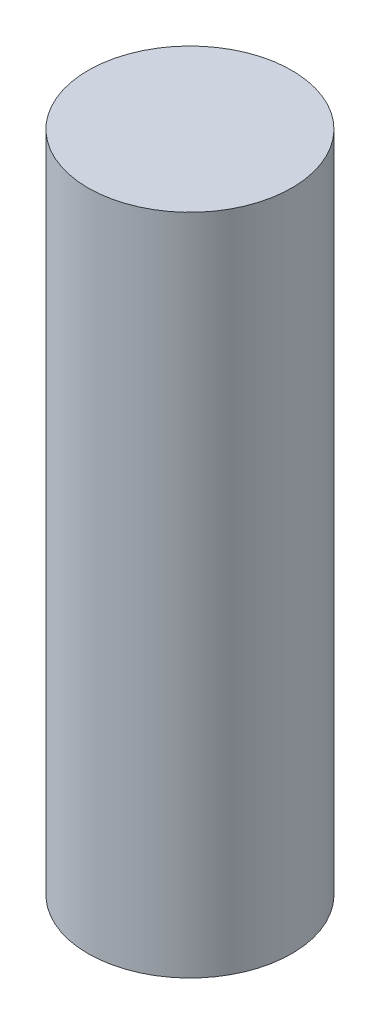
SolidWorks part; units mm, degrees
material "Silicon Dioxide"
ref_plane "Front Plane" through (0, 0, 0) normal (0, 0, 1) x (1, 0, 0)
ref_plane "Top Plane" through (0, 0, 0) normal (0, 1, 0) x (1, 0, 0)
ref_plane "Right Plane" through (0, 0, 0) normal (1, 0, 0) x (0, 0, -1)
sketch "Sketch1" plane through (0, 0, 0) normal (0, 1, 0) x (1, 0, 0)
  circle A0 centre (0, 0) radius 10.775
  dimension "D1" = 21.55
extrude "Boss-Extrude1" add sketch "Sketch1" along normal blind 70.15
equation "\"CellDiameter\"=0.848425"
equation "\"D1@Sketch1\"=\"CellDiameter\""
equation "\"CellHeight\"=2.76181"
equation "\"D1@Boss-Extrude1\"=\"CellHeight\""
